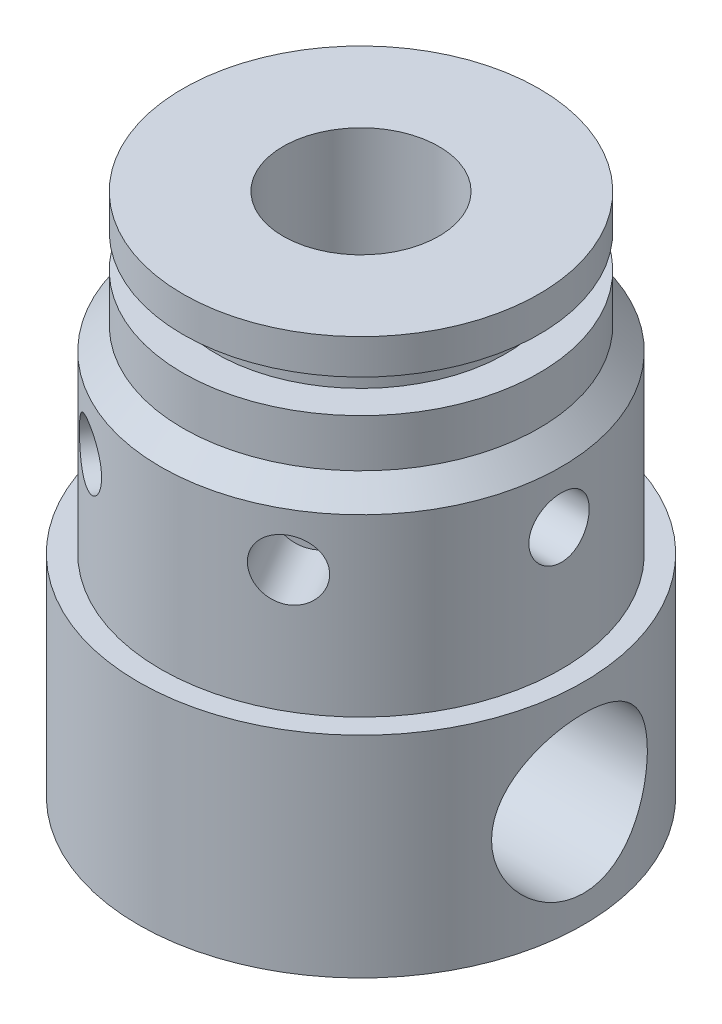
SolidWorks part; units mm, degrees
ref_plane "Front Plane" through (0, 0, 0) normal (0, 0, 1) x (1, 0, 0)
ref_plane "Top Plane" through (0, 0, 0) normal (0, 1, 0) x (1, 0, 0)
ref_plane "Right Plane" through (0, 0, 0) normal (1, 0, 0) x (0, 0, -1)
sketch "Sketch1" plane through (0, 0, 0) normal (0, 0, 1) x (1, 0, 0)
  line L0 (0, -18.6906) -> (15.875, -18.6906)
  line L1 (15.875, -18.6906) -> (15.875, -3.6906)
  line L2 (15.875, -3.6906) -> (14.29, -3.6906)
  line L3 (12.7, 10.3994) -> (12.7, 13.8094)
  line L4 (12.7, 13.8094) -> (10.3188, 13.8094)
  line L5 (10.3188, 13.8094) -> (10.3188, 16.1906)
  line L6 (10.3188, 16.1906) -> (12.7, 16.1906)
  line L7 (12.7, 16.1906) -> (12.7, 18.6906)
  line L13 (0, 18.6906) -> (0, -18.6906)
  line L14 (0, -8.095) -> (0, 15.2312) construction
  line L15 (12.7, 17.1677) -> (12.7, -7.7109) construction
  line L16 (10.3188, 15) -> (12.7, 15) construction
  line L19 (14.29, -3.6906) -> (14.29, 8.8094)
  line L20 (14.29, 8.8094) -> (12.7, 10.3994)
  line L21 (0, 18.6906) -> (12.7, 18.6906)
  line L22 (10.3188, 13.8094) -> (10.3188, -3.6906) construction
  line L23 (10.3188, -3.6906) -> (14.29, -3.6906) construction
  point P18 (0, 0)
  dimension "D1" = 12.7
  dimension "D2" = 12.5
  dimension "D3" = 31.75
  dimension "D4" = 15
  dimension "D5" = 135
  dimension "D6" = 2.5
  dimension "D7" = 17.5
  dimension "D8" = 1.59
  dimension "D9" = 2.3812
revolve "Revolve1" add sketch "Sketch1" angle 360 about L14
sketch "Sketch2" plane through (0, 0, 0) normal (1, 0, 0) x (0, 0, -1)
  line L0 (0, -3.6906) -> (0, -18.6906) construction
  line L1 (15.875, -3.6906) -> (-15.875, -3.6906) construction
  line L2 (-15.875, -18.6906) -> (15.875, -18.6906) construction
  circle A0 centre (0, -11.1906) radius 5.5562
  dimension "D1" = 11.1125
extrude "Cut-Extrude1" cut sketch "Sketch2" against normal through all both and the other way through all
ref_plane "Plane1" through (14.29, 0, 0) normal (1, 0, 0) x (0, 0, -1)
sketch "Sketch4" plane through (14.29, 0, 0) normal (1, 0, 0) x (0, 0, -1)
  line L0 (0, -3.6906) -> (0, 13.8094) construction
  line L1 (15.875, -3.6906) -> (-15.875, -3.6906) construction
  line L2 (12.7, 13.8094) -> (-12.7, 13.8094) construction
  circle A0 centre (0, 5.0594) radius 2.15
  dimension "D1" = 4.3
extrude "Cut-Extrude3" cut sketch "Sketch4" against normal blind 5
pattern_circular "CirPattern1" count 6 over 360 about axis through (0, 0, 0) along (0, 1, 0) of "Cut-Extrude3"
sketch "Sketch6" plane through (0, 18.6906, 0) normal (0, 1, 0) x (1, 0, 0)
  circle A0 centre (0, 0) radius 5.555
  dimension "D1" = 11.11
extrude "Cut-Extrude4" cut sketch "Sketch6" against normal up to surface (29.7634 mm away)
